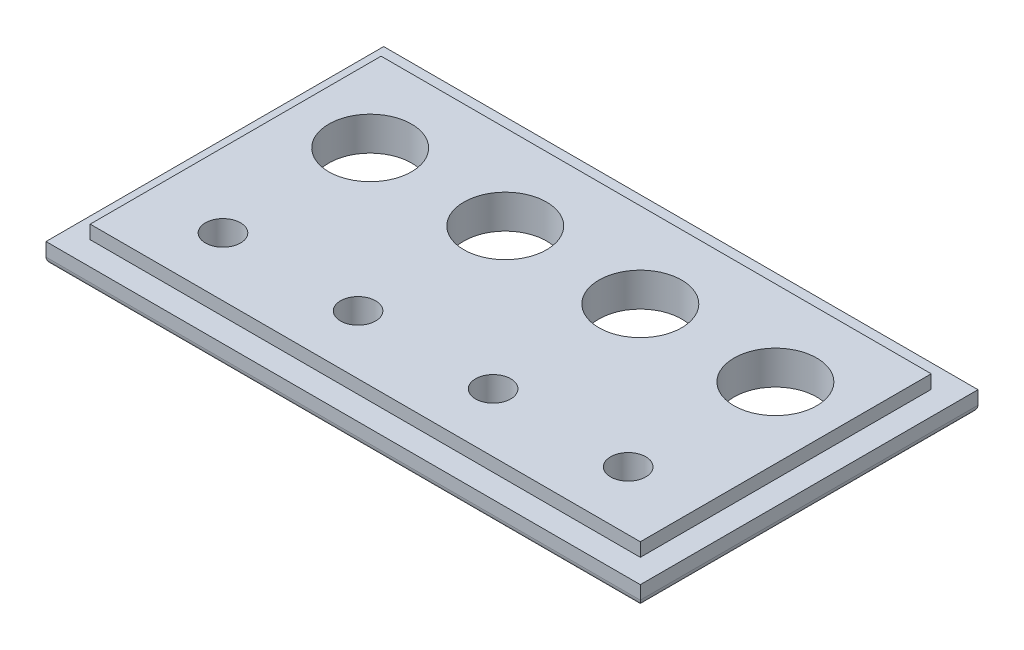
SolidWorks part; units mm, degrees
material "ABS"
ref_plane "Front Plane" through (0, 0, 0) normal (0, 0, 1) x (1, 0, 0)
ref_plane "Top Plane" through (0, 0, 0) normal (0, 1, 0) x (1, 0, 0)
ref_plane "Right Plane" through (0, 0, 0) normal (1, 0, 0) x (0, 0, -1)
sketch "Sketch4" plane through (0, 0, 0) normal (0, 1, 0) x (1, 0, 0)
  line L0 (-31.86, 50) -> (-44, 50) construction
  line L3 (-44, 50) -> (44, 50)
  line L4 (-44, 50) -> (-44, 0)
  line L5 (-44, 0) -> (44, 0)
  line L6 (44, 50) -> (44, 0)
  line L8 (-41, 47) -> (41, 47)
  line L9 (-41, 47) -> (-41, 3)
  line L10 (-41, 3) -> (41, 3)
  line L11 (41, 47) -> (41, 3)
  point P3 (0, 0)
  point P14 (-44, 25)
  point P15 (0, 0)
  point P16 (0, 0)
  dimension "D1" = 3
  dimension "D2" = 3
  dimension "D3" = 3
  dimension "D4" = 3
extrude "Boss-Extrude2" add sketch "Sketch4" along normal blind 3 separate body
sketch "Sketch6" plane through (0, 3, 0) normal (0, 1, 0) x (1, 0, 0)
  line L0 (-44, 0) -> (44, 0) construction
  line L1 (-40.9566, 46.5735) -> (40.5, 46.5735)
  line L2 (-40.9566, 46.5735) -> (-40.9566, 3.5)
  line L3 (-40.9566, 3.5) -> (40.5, 3.5)
  line L4 (40.5, 46.5735) -> (40.5, 3.5)
  line L5 (-40.9566, 46.5735) -> (40.5, 3.5) construction
  line L6 (-40.9566, 3.5) -> (40.5, 46.5735) construction
  line L7 (44, 50) -> (44, 0) construction
  point P0 (-0.2283, 25.0367)
  dimension "D1" = 3.5
  dimension "D2" = 3.5
extrude "Boss-Extrude3" add sketch "Sketch6" along normal blind 2
sketch "Sketch5" plane through (0, 3, 0) normal (0, 1, 0) x (-1, 0, 0)
  line L0 (-44, -34) -> (44, -34) construction
  line L1 (-44, -50) -> (-44, 0) construction
  line L2 (44, -50) -> (44, 0) construction
  line L3 (-30, -34) -> (-30, -50) construction
  line L4 (44, -50) -> (-44, -50) construction
  line L5 (-44, -25) -> (44, -25) construction
  line L6 (-44, -12.2068) -> (44, -12.2068) construction
  circle A0 centre (-30, -34) radius 6.125
  circle A1 centre (-10, -34) radius 6.125
  circle A2 centre (10, -34) radius 6.125
  circle A3 centre (30, -34) radius 6.125
  circle A4 centre (-30, -12.2068) radius 2.6
  circle A5 centre (-10, -12.2068) radius 2.6
  circle A6 centre (10, -12.2068) radius 2.6
  circle A7 centre (30, -12.2068) radius 2.6
  dimension "D2" = 12.25
  dimension "D4" = 16
  dimension "D6" = 5.2
  dimension "D3" = 14
  dimension "D5" = 4
  dimension "D1" = 4
extrude "Cut-Extrude1" cut sketch "Sketch5" along normal through all both and the other way through all
fillet "Fillet1" radius 1 4 edges at (0, 0, 0) (44, 0, -25) (0, 0, -50) (-44, 0, -25)
